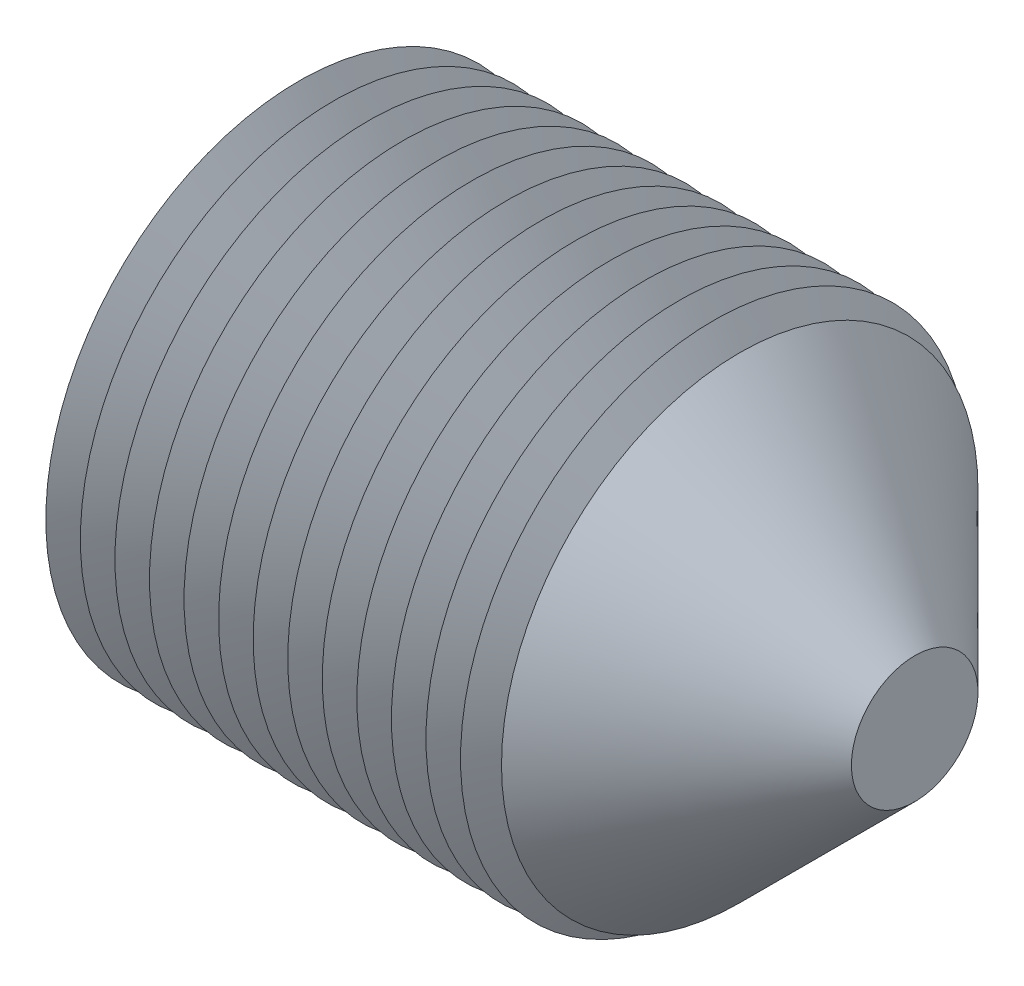
SolidWorks part; units mm, degrees
ref_plane "前视基准面" through (0, 0, 0) normal (0, 0, 1) x (1, 0, 0)
ref_plane "上视基准面" through (0, 0, 0) normal (0, 1, 0) x (1, 0, 0)
ref_plane "右视基准面" through (0, 0, 0) normal (1, 0, 0) x (0, 0, -1)
sketch "草图1" plane through (0, 0, 0) normal (0, 0, 1) x (1, 0, 0)
  line B0 (10, 0) -> (0, 0)
  line B1 (0, 0) -> (0, 3.5219)
  line B2 (10, 1) -> (10, 0)
  line B3 (10, 1) -> (7.2361, 3.7639)
  line B4 (0, 3.5219) -> (0.273, 4)
  line B5 (0.546, 3.5219) -> (0.273, 4)
  line B6 (0.546, 3.5219) -> (0.819, 4)
  line B7 (1.092, 3.5219) -> (0.819, 4)
  line B8 (1.092, 3.5219) -> (1.365, 4)
  line B9 (1.638, 3.5219) -> (1.365, 4)
  line B10 (1.638, 3.5219) -> (1.911, 4)
  line B11 (2.184, 3.5219) -> (1.911, 4)
  line B12 (2.184, 3.5219) -> (2.457, 4)
  line B13 (2.73, 3.5219) -> (2.457, 4)
  line B14 (2.73, 3.5219) -> (3.003, 4)
  line B15 (3.276, 3.5219) -> (3.003, 4)
  line B16 (3.276, 3.5219) -> (3.549, 4)
  line B17 (3.822, 3.5219) -> (3.549, 4)
  line B18 (3.822, 3.5219) -> (4.095, 4)
  line B19 (4.368, 3.5219) -> (4.095, 4)
  line B20 (4.368, 3.5219) -> (4.641, 4)
  line B21 (4.914, 3.5219) -> (4.641, 4)
  line B22 (4.914, 3.5219) -> (5.187, 4)
  line B23 (5.46, 3.5219) -> (5.187, 4)
  line B24 (5.46, 3.5219) -> (5.7329, 4)
  line B25 (6.0059, 3.5219) -> (5.7329, 4)
  line B26 (6.0059, 3.5219) -> (6.2789, 4)
  line B27 (6.5519, 3.5219) -> (6.2789, 4)
  line B28 (6.5519, 3.5219) -> (6.8249, 4)
  line B29 (7.0979, 3.5219) -> (6.8249, 4)
  line B30 (7.0979, 3.5219) -> (7.2361, 3.7639)
sketch_block_instance "A$C2A4A2F9E-1"
sketch_block "A$C2A4A2F9E"
revolve "旋转1" add sketch "草图1" angle 360 about L0
